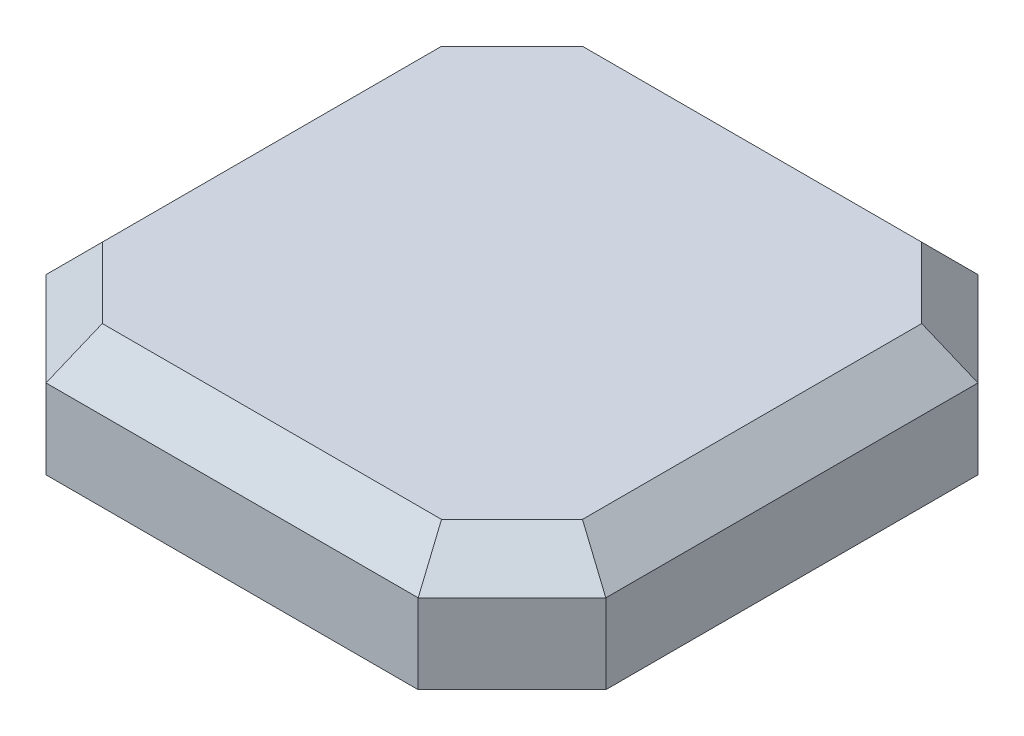
SolidWorks part; units mm, degrees
ref_plane "前视基准面" through (0, 0, 0) normal (0, 0, 1) x (1, 0, 0)
ref_plane "上视基准面" through (0, 0, 0) normal (0, 1, 0) x (1, 0, 0)
ref_plane "右视基准面" through (0, 0, 0) normal (1, 0, 0) x (0, 0, -1)
other "Configuration Table"
sketch "草图1" plane through (0, 0, 0) normal (0, 1, 0) x (1, 0, 0)
  line L0 (-18.4036, 20.2102) -> (-25.4746, 13.1392)
  line L1 (-18.4036, -21.9898) -> (9.6543, -21.9898)
  line L2 (-25.4746, -14.9187) -> (-25.4746, 13.1392)
  line L3 (-18.4036, 20.2102) -> (9.6543, 20.2102)
  line L4 (16.7254, -14.9187) -> (16.7254, 13.1392)
  line L5 (-22.8476, -17.5457) -> (14.0983, 15.7662) construction
  line L6 (-20.3249, 18.2889) -> (11.5756, -20.0684) construction
  line L7 (16.7254, 13.1392) -> (9.6543, 20.2102)
  line L8 (9.6543, -21.9898) -> (16.7254, -14.9187)
  line L9 (-25.4746, -14.9187) -> (-18.4036, -21.9898)
  point P0 (-4.3746, -0.8898)
  point P13 (-4.3746, -0.8898)
  point P15 (-4.3746, -0.8898)
  dimension "D1" = 10
  dimension "D2" = 42.2
  dimension "D3" = 135
extrude "凸台-拉伸1" add sketch "草图1" along normal blind 9
chamfer "倒角1" distance 3 angle 45 8 edges at (13.1898, 9, -16.6747) (16.7254, 9, 0.8898) (13.1898, 9, 18.4542) (-4.3746, 9, 21.9898) (-21.9391, 9, 18.4542) (-25.4746, 9, 0.8898) (-21.9391, 9, -16.6747) (-4.3746, 9, -20.2102)
sketch "草图3" plane through (0, 0, 0) normal (0, -1, 0) x (1, 0, 0)
  line L0 (-4.3746, 21.9898) -> (-4.3746, -20.2102) construction
  line L1 (-18.4036, 21.9898) -> (9.6543, 21.9898) construction
  line L2 (9.6543, -20.2102) -> (-18.4036, -20.2102) construction
  circle A0 centre (9.4348, 14.6992) radius 3
  circle A1 centre (9.4348, 14.6992) radius 2.5
  circle A2 centre (9.4348, -12.9197) radius 3
  circle A3 centre (9.4348, -12.9197) radius 2.5
  circle A4 centre (-18.1841, -12.9197) radius 3
  circle A5 centre (-18.1841, -12.9197) radius 2.5
  circle A6 centre (-18.1841, 14.6992) radius 3
  circle A7 centre (-18.1841, 14.6992) radius 2.5
  point P9 (-4.3746, 0.8898)
  point P22 (-4.3746, 0.8898)
  dimension "D1" = 6
  dimension "D2" = 5
  dimension "D3" = 4
extrude "凸台-拉伸2" add sketch "草图3" along normal blind 1
